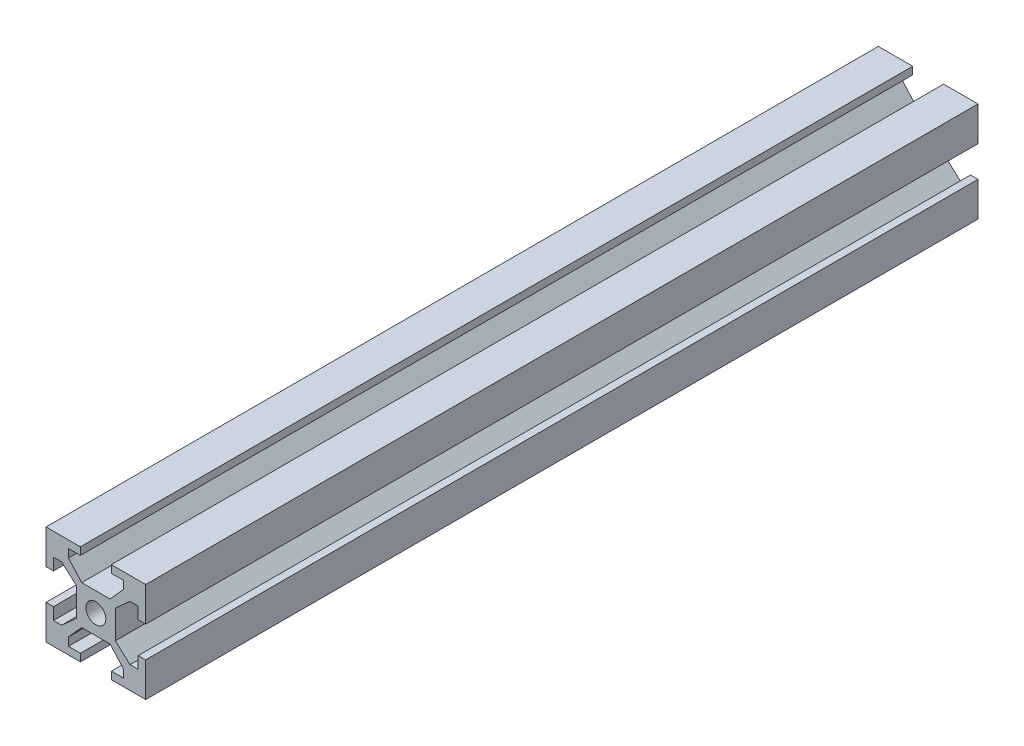
SolidWorks part; units mm, degrees
material "6063-T6"
ref_plane "Front Plane" through (0, 0, 0) normal (0, 0, 1) x (1, 0, 0)
ref_plane "Top Plane" through (0, 0, 0) normal (0, 1, 0) x (1, 0, 0)
ref_plane "Right Plane" through (0, 0, 0) normal (1, 0, 0) x (0, 0, -1)
sketch "Sketch1" plane through (0, 0, 0) normal (0, 0, 1) x (1, 0, 0)
  line L0 (10, 10) -> (4.6104, 10) construction
  line L1 (10, 10) -> (10, 4.6104) construction
  line L2 (10, -10) -> (10, -4.6104) construction
  line L3 (10, -10) -> (4.6104, -10) construction
  line L4 (10, 10) -> (10, 4.6104)
  line L5 (6.8607, 5.5) -> (8.5, 5.5)
  line L6 (5.5, 8.5) -> (5.5, 6.8607)
  line L7 (10, 10) -> (4.6104, 10)
  line L8 (10, 10) -> (10, 4.6104)
  line L9 (6.8607, 5.5) -> (3.9, 2.8393)
  line L10 (5.5, 6.8607) -> (2.8393, 3.9)
  line L13 (8.5, 3.1) -> (8.5, 5.5)
  line L14 (3.1, 8.5) -> (5.5, 8.5)
  line L15 (-6.8607, 5.5) -> (-8.5, 5.5)
  line L16 (6.8607, -5.5) -> (8.5, -5.5)
  line L17 (3.1, -8.5) -> (5.5, -8.5)
  line L18 (8.5, -3.1) -> (8.5, -5.5)
  line L21 (-3.9, 0.5196) -> (-3.9, -0.5196)
  line L22 (-0.5196, 3.9) -> (0.5196, 3.9)
  line L23 (3.9, 0.5196) -> (3.9, -0.5196)
  line L24 (-0.5196, -3.9) -> (0.5196, -3.9)
  line L25 (3.9, 0.5196) -> (3.9, 2.8393)
  line L26 (2.8393, 3.9) -> (0.5196, 3.9)
  line L27 (3.9, -2.8393) -> (3.9, -0.5196)
  line L28 (2.8393, -3.9) -> (0.5196, -3.9)
  line L29 (5.5, -6.8607) -> (2.8393, -3.9)
  line L30 (6.8607, -5.5) -> (3.9, -2.8393)
  line L31 (10, -10) -> (10, -4.6104)
  line L32 (10, -10) -> (4.6104, -10)
  line L33 (5.5, -8.5) -> (5.5, -6.8607)
  line L34 (-6.8607, -5.5) -> (-8.5, -5.5)
  line L35 (10, -10) -> (10, -4.6104)
  line L36 (0, 0) -> (0, 8.5) construction
  line L37 (-10, -10) -> (-4.6104, -10) construction
  line L38 (-10, -10) -> (-10, -4.6104) construction
  line L39 (-10, 10) -> (-10, 4.6104) construction
  line L40 (-10, 10) -> (-4.6104, 10) construction
  line L41 (-10, -10) -> (-10, -4.6104)
  line L42 (-3.1, -8.5) -> (-3.1, -10)
  line L43 (-5.5, -8.5) -> (-5.5, -6.8607)
  line L44 (-10, -10) -> (-4.6104, -10)
  line L45 (-10, -10) -> (-10, -4.6104)
  line L46 (-6.8607, -5.5) -> (-3.9, -2.8393)
  line L47 (-5.5, -6.8607) -> (-2.8393, -3.9)
  line L48 (-2.8393, -3.9) -> (-0.5196, -3.9)
  line L49 (-3.9, -2.8393) -> (-3.9, -0.5196)
  line L50 (-2.8393, 3.9) -> (-0.5196, 3.9)
  line L51 (-3.9, 0.5196) -> (-3.9, 2.8393)
  line L52 (-3.1, -10) -> (-4.6104, -10)
  line L53 (3.1, -8.5) -> (3.1, -10)
  line L54 (3.1, -10) -> (4.6104, -10)
  line L55 (8.5, -3.1) -> (10, -3.1)
  line L58 (-8.5, -3.1) -> (-8.5, -5.5)
  line L59 (-3.1, -8.5) -> (-5.5, -8.5)
  line L60 (-10, -10) -> (10, -10) construction
  line L61 (-10, -10) -> (-10, 10) construction
  line L62 (-3.1, 8.5) -> (-5.5, 8.5)
  line L63 (-8.5, 3.1) -> (-8.5, 5.5)
  line L66 (-5.5, 6.8607) -> (-2.8393, 3.9)
  line L67 (-6.8607, 5.5) -> (-3.9, 2.8393)
  line L68 (-10, 10) -> (-10, 4.6104)
  line L69 (-10, 10) -> (-4.6104, 10)
  line L70 (-5.5, 8.5) -> (-5.5, 6.8607)
  line L71 (-10, 10) -> (10, 10) construction
  line L72 (-10, 10) -> (-10, 4.6104)
  line L73 (10, -10) -> (10, 10) construction
  line L74 (-10, -10) -> (10, 10) construction
  line L75 (-10, 10) -> (10, -10) construction
  line L76 (10, -3.1) -> (10, -4.6104)
  line L77 (8.5, 3.1) -> (10, 3.1)
  line L78 (10, 3.1) -> (10, 4.6104)
  line L79 (3.1, 8.5) -> (3.1, 10)
  line L80 (3.1, 10) -> (4.6104, 10)
  line L81 (-3.1, 8.5) -> (-3.1, 10)
  line L82 (-3.1, 10) -> (-4.6104, 10)
  line L83 (-8.5, 3.1) -> (-10, 3.1)
  line L84 (-10, 3.1) -> (-10, 4.6104)
  line L85 (-8.5, -3.1) -> (-10, -3.1)
  line L86 (-10, -3.1) -> (-10, -4.6104)
  circle A0 centre (0, 0) radius 2
  dimension "D7" = 4
  dimension "D1" = 20
  dimension "D2" = 5.3896
  dimension "D3" = 4.5
  dimension "D5" = 1.5
  dimension "D6" = 1.5104
  dimension "D8" = 5.5
  dimension "D11" = 2.3197
  dimension "D12" = 7.8
  dimension "D13" = 7.8
  dimension "D14" = 1.5
  dimension "D15" = 2.6607
extrude "Boss-Extrude1" add sketch "Sketch1" along normal mid plane 167
